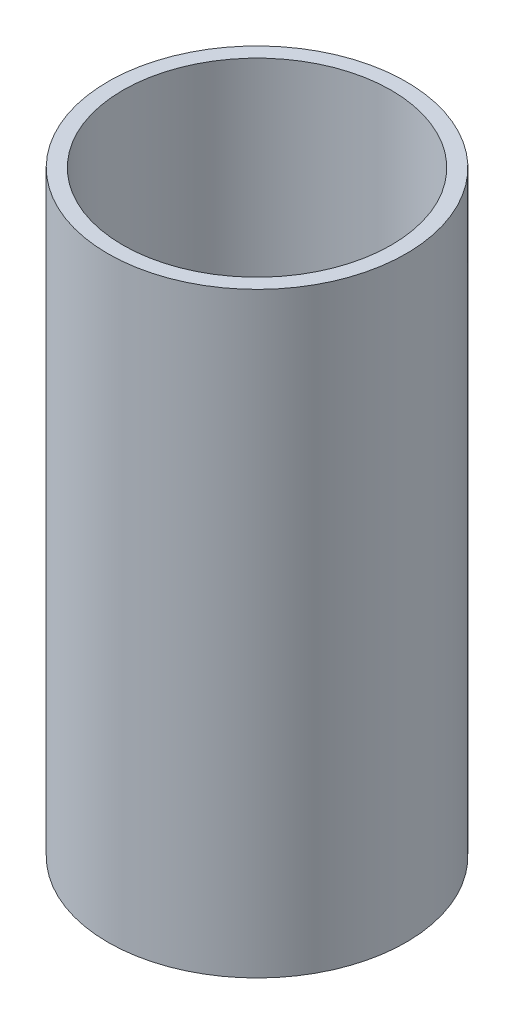
SolidWorks part; units mm, degrees
ref_plane "Front Plane" through (0, 0, 0) normal (0, 0, 1) x (1, 0, 0)
ref_plane "Top Plane" through (0, 0, 0) normal (0, 1, 0) x (1, 0, 0)
ref_plane "Right Plane" through (0, 0, 0) normal (1, 0, 0) x (0, 0, -1)
sketch "Sketch1" plane through (0, 0, 0) normal (0, 1, 0) x (1, 0, 0)
  circle A0 centre (0, 0) radius 50
  circle A1 centre (0, 0) radius 45
extrude "Boss-Extrude1" add sketch "Sketch1" along normal blind 200
